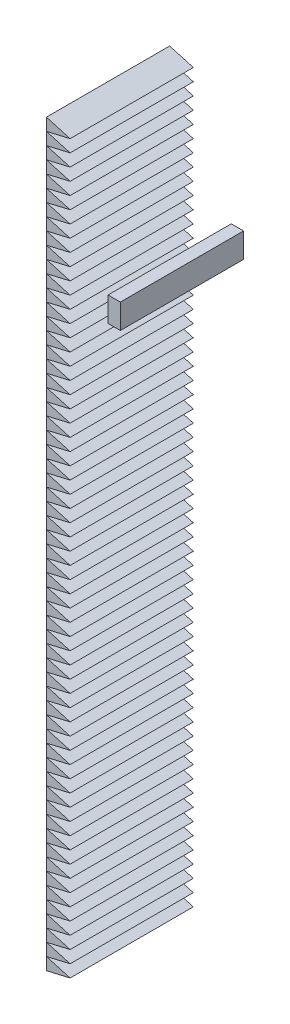
SolidWorks part; units mm, degrees
ref_plane "前基準面" through (0, 0, 0) normal (0, 0, 1) x (1, 0, 0)
ref_plane "上基準面" through (0, 0, 0) normal (0, 1, 0) x (1, 0, 0)
ref_plane "右基準面" through (0, 0, 0) normal (1, 0, 0) x (0, 0, -1)
sketch "草圖2" plane through (0, 0, 0) normal (0, 0, 1) x (1, 0, 0)
  line L1 (50, 500) -> (60, 500)
  line L2 (50, 500) -> (50, 480)
  line L3 (50, 480) -> (60, 480)
  line L4 (60, 500) -> (60, 480)
  dimension "D1" = 20
  dimension "D2" = 10
  dimension "D3" = 50
  dimension "D4" = 480
extrude "填料-伸長2" add sketch "草圖2" along normal blind 100 separate body
sketch "草圖1" plane through (0, 0, 0) normal (0, 0, 1) x (1, 0, 0)
  line L0 (0, 0) -> (0, 10)
  line L1 (0, 10) -> (19.2252, 4.4873)
  line L3 (19.2252, 4.4873) -> (0, 0)
  dimension "D1" = 10
  dimension "D2" = 20
  dimension "D4" = 74
extrude "填料-伸長1" add sketch "草圖1" along normal blind 100
pattern_linear "直線複製排列1" count 60 spacing 10 along (0, 1, 0) of "填料-伸長1"
